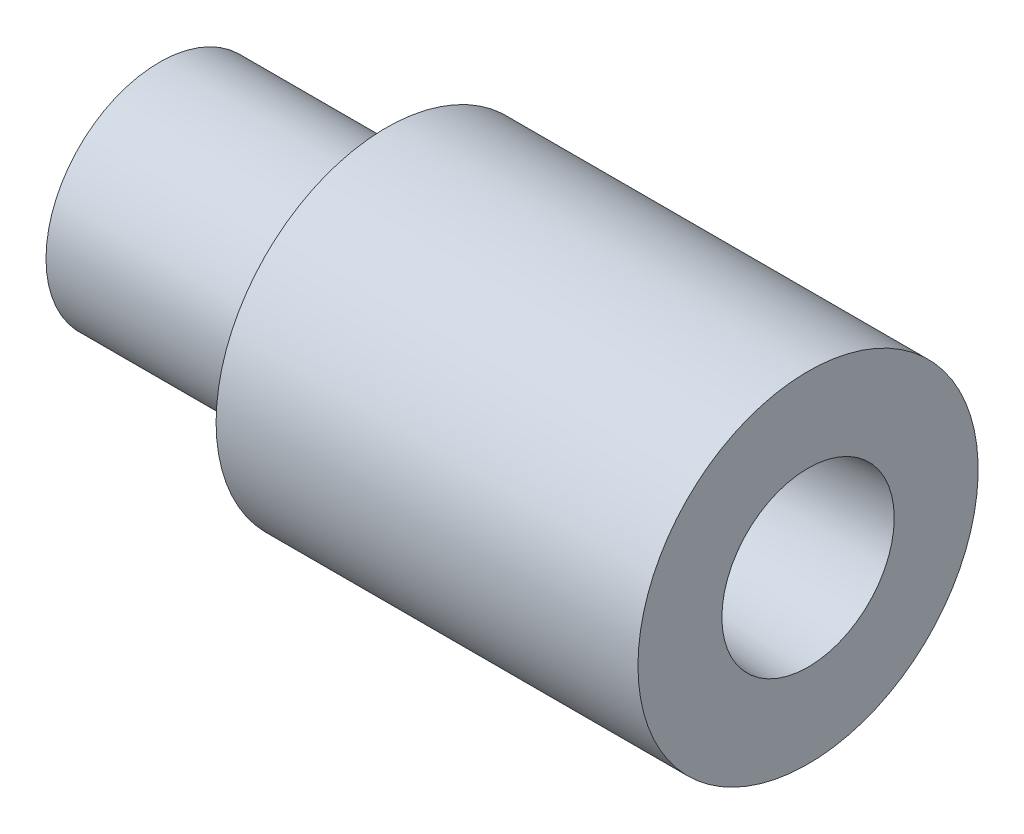
SolidWorks part; units mm, degrees
ref_plane "Front Plane" through (0, 0, 0) normal (0, 0, 1) x (1, 0, 0)
ref_plane "Top Plane" through (0, 0, 0) normal (0, 1, 0) x (1, 0, 0)
ref_plane "Right Plane" through (0, 0, 0) normal (1, 0, 0) x (0, 0, -1)
sketch "Sketch1" plane through (0, 0, 0) normal (0, 1, 0) x (1, 0, 0)
  line L0 (0, 0) -> (0, 2.286) construction
  line L1 (0, 2.286) -> (0, 6.35)
  line L2 (12.7, 9.525) -> (36.3237, 9.525)
  line L3 (36.3237, 9.525) -> (36.3237, 4.826)
  line L4 (36.3237, 4.826) -> (0, 2.286)
  line L5 (0, 0) -> (36.3237, 0) construction
  line L6 (36.3237, 0) -> (36.3237, 4.826) construction
  line L8 (12.7, 6.35) -> (12.7, 9.525)
  line L12 (0, 6.35) -> (12.7, 6.35)
  dimension "D1" = 2.286
  dimension "D2" = 4.826
  dimension "D3" = 4
  dimension "D4" = 9.525
  dimension "D5" = 6.35
  dimension "D6" = 12.7
revolve "Revolve1" add sketch "Sketch1" angle 360 about L5
equation "\"z\" = 8\t\t\t\t'number of blades"
equation "\"de\" = 0.43in\t\t\t'entrance eye diameter"
equation "\"de_length\" = 4mm\t\t'entrance eye consistent length"
equation "\"d_exit\" = 0.18in \t\t'throat aka d1"
equation "\"d2\" = 2.1in \t\t\t'outer diameter of the impeller"
equation "\"b2\" = .2in\t\t\t'tip height from disc surface at d2; slightly higher than d_exit"
equation "\"b1\" = \"b2\" + (\"d2\"/2 - \"de\"/2)*tan(\"theta\") \t\t\t'tip height from disc surface at inlet eye"
equation "\"theta\" = 12\t\t\t'angle of blades from inner to outer "
equation "\"ae\" = 3.14*(\"de\"^2)/4\t\t'entrance eye area'"
equation "\"ce\" = 3.14*\"de\"\t\t'entrance eye circumference"
equation "\"av_ratio\" = .325\t\t'ratio of av/ae at N_s of 470, range is .275 to .375, .325 ideal. High ratio means bigger area means smaller blades"
equation "\"av\" = \"ae\"*\"av_ratio\"\t\t'area between just two blades"
equation "\"s_open\" = \"av\"/\"b1\"\t\t'width of open area"
equation "\"s\"=\"ce\" - \"z\"*\"s_open\""
equation "\"min blade thickness\" = .15in"
equation "\"bearing OD\" = 30mm"
equation "\"bearing ID\"= 10mm"
equation "\"bearing depth\"= 9mm"
equation "\"bearing outer race thickness\"= 1mm"
equation "\"bearing inner race thickness\"= 1mm"
equation "\"bearing bore\" = \"bearing depth\" + 1mm"
equation "\"lower seal OD\" = .917in\t\t'this is https://www.mcmaster.com/#9281k121/=174001b"
equation "\"lower seal ID\"= .375in"
equation "\"lower seal depth\" = .625in + .218in"
equation "\"lower seal bore\" = \"lower seal depth\" + 1mm"
equation "\"upper seal OD\" = 1.125in\t'this is https://www.mcmaster.com/#5154t33/=173zuau, needs to be visually inspected before machining!"
equation "\"upper seal ID\"= 0.625in"
equation "\"upper seal depth\"= .25in\t'aka height; these values need to be confirmed by inspection!! We may want to compress the height."
equation "\"upper seal bore\" = \"upper seal depth\" + 1mm"
equation "\"big o-ring thickness\" = .139in"
equation "\"big o-ring OD\" = 2.734in"
equation "\"big o-ring ID\" = 3.012in"
equation "\"big o-ring groove depth\" = \"big o-ring thickness\"*4/5"
equation "\"impeller center height\" = \"impeller base thickness\" + \"b1\"\t'impeller height at de"
equation "\"impeller outer height\" = \"impeller base thickness\" + \"b2\"\t'impeller height at de"
equation "\"impeller upper clearance\"= .5mm"
equation "\"impeller horizontal clearance\"= (\"d2\"*1.15 - \"d2\")/2 \t\t'clearance based on D2-D3 ratio for circular volute, ranges 1.15 to 1.2"
equation "\"impeller bottom clearance\"= .5mm"
equation "\"impeller base thickness\"= 2mm"
equation "\"impeller dowel diameter\" = 2mm"
equation "\"impeller bolt head diameter\" = \"m4 head bore diameter\""
equation "\"impeller bolt head depth\" = 4mm"
equation "\"impeller bolt stop depth\" = 3mm"
equation "\"impeller bolt bore\" = \"m4 clearance\""
equation "\"impeller shaft bore depth\" = 12mm"
equation "\"impeller shaft bore\" = 8mm"
equation "\"impeller boss depth\" = \"impeller shaft bore depth\"+\"impeller bolt stop depth\"+\"impeller bolt head depth\"-\"impeller base thickness\""
equation "\"impeller boss diameter\" = \"upper seal ID\""
equation "\"impeller dowel length\" = 2mm*2 + \"impeller shaft bore\""
equation "\"coupler motor shaft hole ID\"= 8mm"
equation "\"coupler OD\"= 17mm"
equation "\"coupler length\"= 25mm"
equation "\"motor OD\" = 64mm"
equation "\"motor shaft diameter\"= 8mm"
equation "\"motor shaft pride\"= 32mm"
equation "\"motor to bearing plate distance\" = \"motor shaft pride\" + 2mm +\"coupler length\"/2"
equation "\"square plate bolt bore\" = \"m8 clearance\""
equation "\"square plate bolt head diameter\" = 13.5mm"
equation "\"square plate bolt head depth\" = 8mm"
equation "\"square plate bolt pattern diameter\"= 3.5in"
equation "\"motor mount center bore\"= \"coupler OD\"+ 4mm"
equation "\"motor mount post radius\"= ( 3 * \"square plate bolt bore\" ) / 2"
equation "\"motor mount m4 screw hole diameter\"= 4mm"
equation "\"motor mount m4 head diameter\"= 7.25mm"
equation "\"motor mount m4 head depth\"= 4mm"
equation "\"motor mount m4 pattern diamater\" = 30mm"
equation "\"motor mount plate thickness\"= 8mm + \"motor mount m4 head depth\""
equation "\"bearing plate stop ID\" = \"bearing OD\" - 4mm"
equation "\"bearing plate stop depth\" = 3mm"
equation "\"bearing plate thickness\" = \"bearing bore\" + \"bearing plate stop depth\" + \"shaft bearing stop length\""
equation "\"lower seal plate lip depth\" = 2mm"
equation "\"lower seal plate lip ID\" = \"lower seal OD\" - 3mm"
equation "\"lower seal plate thickness\" = \"lower seal plate lip depth\" + \"lower seal bore\""
equation "\"shaft coupler section diameter\" = 8mm"
equation "\"shaft coupler section length\" = \"motor to bearing plate distance\" - \"motor shaft pride\" - 2mm"
equation "\"shaft bearing section diameter\" = \"bearing ID\""
equation "\"shaft bearing section length\" = \"bearing plate stop depth\" + \"bearing depth\""
equation "\"shaft bearing stop diameter\" = \"bearing ID\" + 4mm"
equation "\"shaft bearing stop length\" = 3mm"
equation "\"shaft lower seal section diameter\" = \"lower seal ID\""
equation "\"shaft lower seal section length\" = \"lower seal plate thickness\" + 1mm"
equation "\"shaft impeller section diameter\" = \"impeller shaft bore\""
equation "\"shaft impeller section length\" = \"upper seal plate thickness\" + \"upper seal plate riser\" + \"impeller bottom clearance\" + \"impeller base thickness\" - \"impeller bolt head depth\" - \"impeller bolt stop depth\""
equation "\"upper seal plate thickness\" = \"upper seal plate pressure hole diameter\"+10mm"
equation "\"upper seal plate lip ID\" = \"upper seal OD\" - 3mm"
equation "\"upper seal plate riser\" = 6.59mm \t\t'this number needs to be read from the housing file"
equation "\"upper seal plate pressure hole diameter\" = .125in\t'this is 1/8 drill "
equation "\"upper seal plate pressure tap diameter\" = .328125in \t'this is 21/64 drill for a 1/8 ANPT tap"
equation "\"upper seal plate pressure tap grip\" = 5mm\t\t'this is the area around the tap so it doesn't crack"
equation "\"upper seal plate pressure tap depth\" = 12mm"
equation "\"impeller cavity center height\"= \"impeller bottom clearance\" + \"impeller upper clearance\" + \"impeller center height\""
equation "\"impeller cavity diameter\"= 2 * \"impeller horizontal clearance\" + \"d2\" \t\t\t\t\t\t\t\t\t'called D3 analytically"
equation "\"impeller cavity outer height\"= \"impeller bottom clearance\" + \"impeller upper clearance\" + \"impeller base thickness\" + \"b2\" \t\t'this is height at impeller diameter d2, not at d3"
equation "\"impeller housing thickness\"= \"impeller housing exit threaded diameter\" + 2*\"impeller housing outlet grip\""
equation "\"impeller housing diameter\" = 4.5in"
equation "\"impeller housing bolt count\" = 8"
equation "\"impeller housing bolt diameter\" = \"m6 clearance\""
equation "\"impeller housing bolt pattern diameter\" = 3.5in"
equation "\"impeller housing threaded inlet diameter\" = 0.71875in \t'this is the 23/32 drill size for 1/2 NPT fitting https://www.mcmaster.com/#50715k269/=176pljy"
equation "\"impeller housing threaded inlet depth\"= .6in"
equation "\"impeller housing exit threaded diameter\"= 0.515625in \t\t'this is the 33/64 drill size for 9/16-18 fitting, expecting swagelok SS-8FK0-1-6STH fitting"
equation "\"impeller housing exit threaded depth\"= 10mm"
equation "\"impeller housing diffuser conical angle\"=10"
equation "\"impeller housing diffuser tangent angle\"=5"
equation "\"impeller housing diffuser final diameter\" = .38in\t\t'aka d2'"
equation "\"impeller housing outlet grip\" = 5mm"
equation "\"end mill size\" = 0.375in\t'for 3/8 endmill"
equation "\"m4 clearance\" = 0.171875in \t'this is 11/64 bit for 4.36mm"
equation "\"m4 tap\" = 0.125in\t\t'this is 1/8 bit for 3.17mm"
equation "\"m4 head bore diameter\" = 7.5mm"
equation "\"m4 head bore depth\" = 5mm\t'actual is ~4mm"
equation "\"m6 clearance\" = 0.234375in\t'this is 15/64 bit = 5.95mm, could use 6mm bit, B bit for 6.04mm or 1/4 bit for 6.35mm"
equation "\"m6 tap\" = 5mm\t\t\t'5mm is appropriate, could use 13/64 or #5,6,7"
equation "\"m6 head bore diameter\" = 11mm\t\t"
equation "\"m6 head bore depth\" = 7mm\t'actual is 6mm"
equation "\"m8 clearance\" = 0.3125in\t'this is 5/16in for 7.93mm, could use 8mm, O,P, or 21/64"
equation "\"m8 tap\" = 0.265625in\t\t'this is 17/64 for 6.746875mm"
equation "\"m8 head bore diameter\" = 14mm"
equation "\"m8 head bore depth\" = 9mm\t'actual is 8mm"
equation "\"D1@Sketch1\"=\"d_exit\"/2"
equation "\"D2@Sketch1\"=\"impeller housing diffuser final diameter\"/2"
equation "\"diffuser cartridge OD\" =.75in"
equation "\"D4@Sketch1\"=\"diffuser cartridge OD\"/2"
